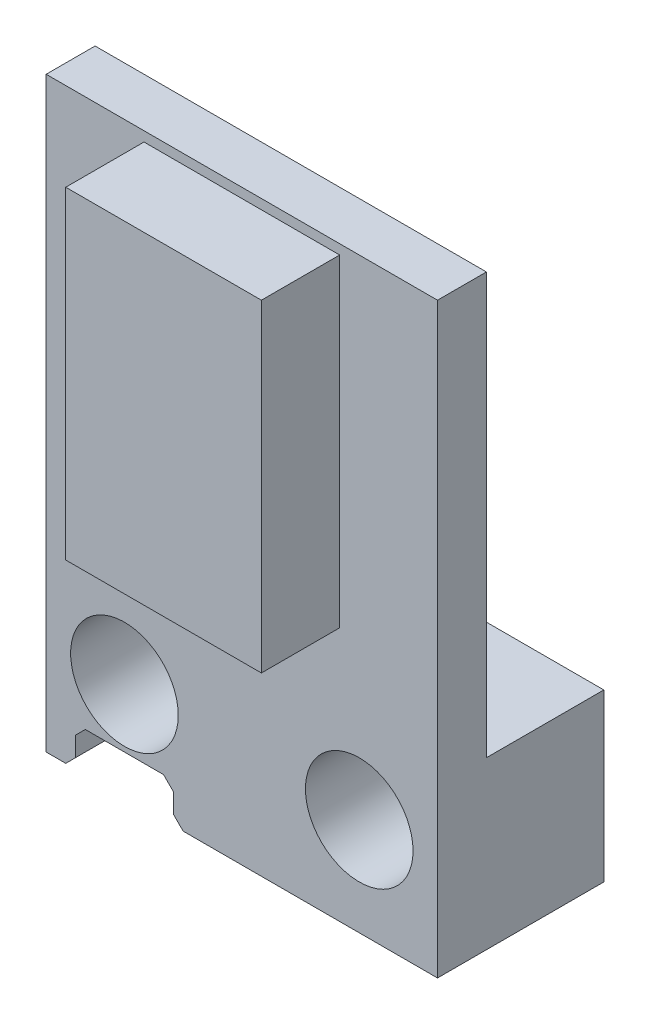
SolidWorks part; units mm, degrees
ref_plane "前视基准面" through (0, 0, 0) normal (0, 0, 1) x (1, 0, 0)
ref_plane "上视基准面" through (0, 0, 0) normal (0, 1, 0) x (1, 0, 0)
ref_plane "右视基准面" through (0, 0, 0) normal (1, 0, 0) x (0, 0, -1)
other "Configuration Table"
sketch "草图1" plane through (0, 0, 0) normal (0, 0, 1) x (1, 0, 0)
  line L1 (-20, -30) -> (20, -30)
  line L2 (-20, -30) -> (-20, 30)
  line L3 (-20, 30) -> (20, 30)
  line L4 (20, -30) -> (20, 30)
  line L5 (-20, -30) -> (20, 30) construction
  line L6 (-20, 30) -> (20, -30) construction
  point P0 (0, 0)
  dimension "D1" = 60
  dimension "D2" = 40
extrude "凸台-拉伸1" add sketch "草图1" along normal blind 5
sketch "草图2" plane through (0, 0, 0) normal (0, 0, -1) x (-1, 0, 0)
  line L0 (20, 30) -> (20, -30) construction
  line L1 (-20, -30) -> (20, -30)
  line L2 (-20, -30) -> (-20, -13)
  line L3 (-20, -13) -> (20, -13)
  line L4 (20, -30) -> (20, -13)
  dimension "D1" = 17
extrude "凸台-拉伸2" add sketch "草图2" along normal blind 12
sketch "草图3" plane through (0, 0, 5) normal (0, 0, 1) x (1, 0, 0)
  line L0 (-20, -20) -> (20, -20) construction
  line L1 (-20, 30) -> (-20, -30) construction
  line L2 (20, -30) -> (20, 30) construction
  line L3 (-20, -30) -> (20, -30) construction
  circle A0 centre (-12, -20) radius 5.5
  circle A1 centre (12, -20) radius 5.5
  dimension "D2" = 11
  dimension "D3" = 11
  dimension "D1" = 10
  dimension "D4" = 8
  dimension "D5" = 8
extrude "切除-拉伸1" cut sketch "草图3" against normal blind 15
sketch "草图4" plane through (0, 0, -10) normal (0, 0, 1) x (1, 0, 0)
  circle A0 centre (-12, -20) radius 3
  circle A1 centre (12, -20) radius 3
  dimension "D1" = 6
  dimension "D2" = 6
extrude "切除-拉伸2" cut sketch "草图4" against normal blind 10
sketch "草图7" plane through (0, 0, 5) normal (0, 0, 1) x (1, 0, 0)
  line L0 (20, 30) -> (-20, 30) construction
  line L1 (-10, -4) -> (10, -4)
  line L2 (-10, -4) -> (-10, 29)
  line L3 (-10, 29) -> (10, 29)
  line L4 (10, -4) -> (10, 29)
  line L5 (-10, -4) -> (10, 29) construction
  line L6 (-10, 29) -> (10, -4) construction
  point P0 (0, 12.5)
  dimension "D1" = 20
  dimension "D2" = 33
  dimension "D3" = 1
extrude "凸台-拉伸4" add sketch "草图7" along normal blind 8
sketch "草图8" plane through (0, 0, 0) normal (0, 0, -1) x (-1, 0, 0)
  line L0 (-20, 30) -> (20, 30) construction
  line L1 (-5, -3) -> (5, -3)
  line L2 (-5, -3) -> (-5, 27)
  line L3 (-5, 27) -> (5, 27)
  line L4 (5, -3) -> (5, 27)
  line L5 (-5, -3) -> (5, 27) construction
  line L6 (-5, 27) -> (5, -3) construction
  point P0 (0, 12)
  dimension "D1" = 3
  dimension "D2" = 30
  dimension "D3" = 10
extrude "切除-拉伸3" cut sketch "草图8" against normal blind 10
sketch "草图9" plane through (0, -4, 0) normal (0, -1, 0) x (1, 0, 0)
  line L0 (-10, 5) -> (10, 5) construction
  line L1 (-5, 5) -> (5, 5)
  line L2 (-5, 5) -> (-5, 9)
  line L3 (-5, 9) -> (5, 9)
  line L4 (5, 5) -> (5, 9)
  point P6 (0, 9)
  dimension "D1" = 10
  dimension "D2" = 4
extrude "切除-拉伸4" cut sketch "草图9" against normal blind 10
sketch "草图10" plane through (0, 0, 5) normal (0, 0, 1) x (1, 0, 0)
  line L0 (-20, -30) -> (20, -30) construction
  line L1 (-17, -30) -> (-7, -30)
  line L2 (-17, -30) -> (-17, -26)
  line L3 (-17, -26) -> (-7, -26)
  line L4 (-7, -30) -> (-7, -26)
  line L5 (-20, 30) -> (-20, -30) construction
  dimension "D1" = 10
  dimension "D2" = 4
  dimension "D3" = 3
extrude "切除-拉伸5" cut sketch "草图10" against normal blind 25
chamfer "倒角1" distance 1 angle 45 4 edges at (-17, -30, -3.5) (-17, -26, -3.5) (-7, -30, -3.5) (-7, -26, -3.5)
